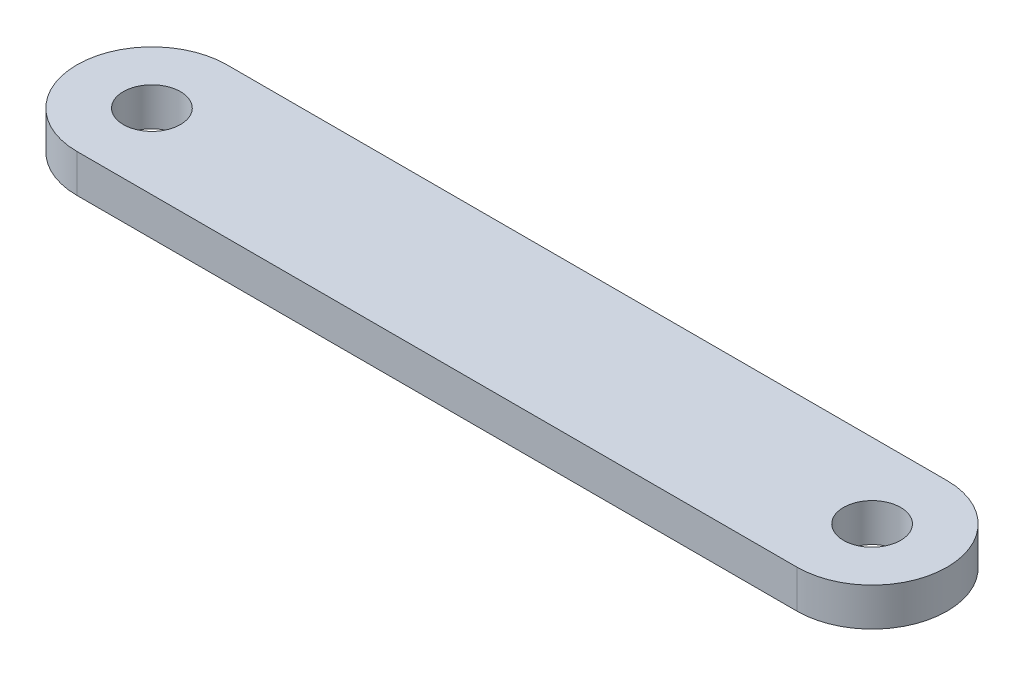
SolidWorks part; units mm, degrees
ref_plane "Front Plane" through (0, 0, 0) normal (0, 0, 1) x (1, 0, 0)
ref_plane "Top Plane" through (0, 0, 0) normal (0, 1, 0) x (1, 0, 0)
ref_plane "Right Plane" through (0, 0, 0) normal (1, 0, 0) x (0, 0, -1)
sketch "Sketch1" plane through (0, 0, 0) normal (0, 1, 0) x (1, 0, 0)
  line L0 (-30, 0) -> (30, 0) construction
  line L1 (-30, 6.25) -> (30, 6.25)
  line L2 (-30, -6.25) -> (30, -6.25)
  arc A0 (-30, 6.25) -> (-30, -6.25) centre (-30, 0) ccw
  arc A1 (30, -6.25) -> (30, 6.25) centre (30, 0) ccw
  circle A2 centre (-30, 0) radius 2.38
  circle A3 centre (30, 0) radius 2.38
  point P2 (0, 0)
  dimension "D3" = 4.76
  dimension "D1" = 12.5
  dimension "D2" = 60
extrude "Boss-Extrude1" add sketch "Sketch1" along normal blind 3.175
